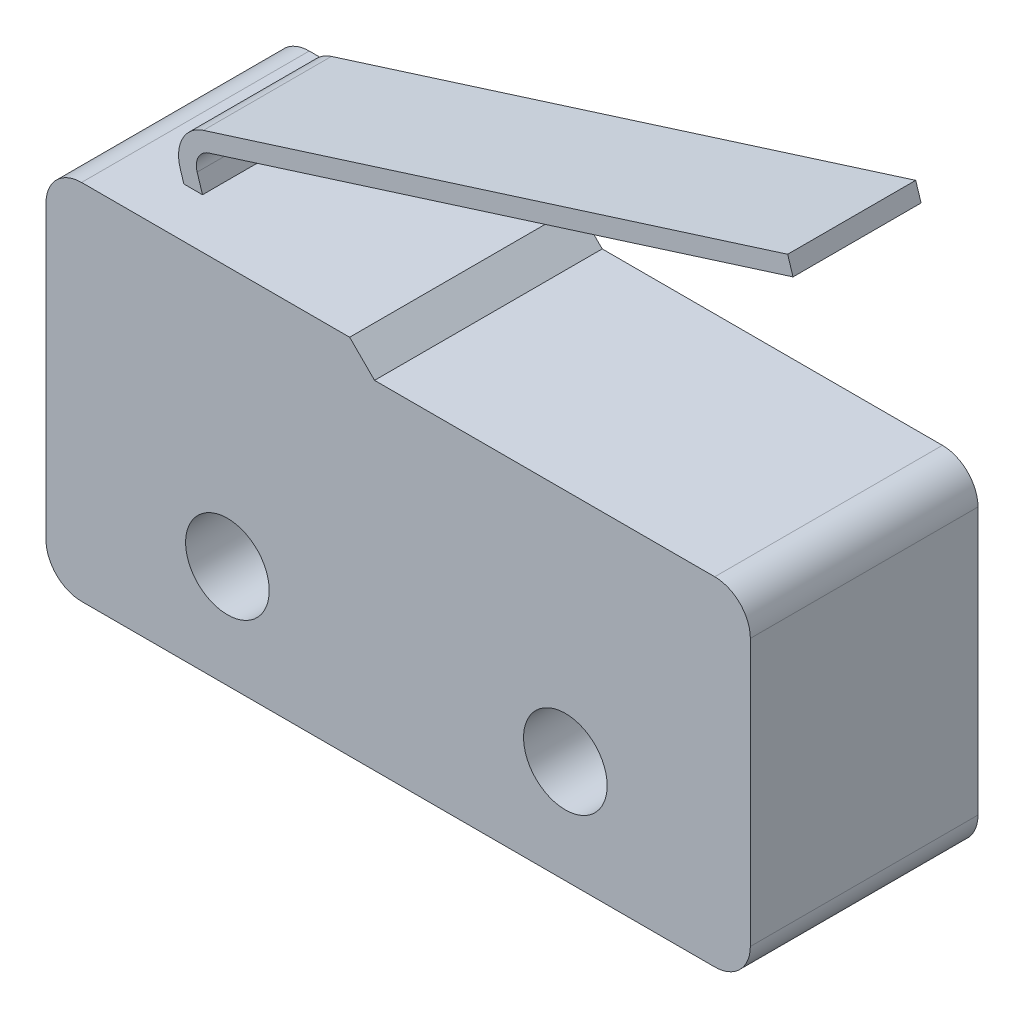
SolidWorks part; units mm, degrees
ref_plane "Plan de face" through (0, 0, 0) normal (0, 0, 1) x (1, 0, 0)
ref_plane "Plan de dessus" through (0, 0, 0) normal (0, 1, 0) x (1, 0, 0)
ref_plane "Plan de droite" through (0, 0, 0) normal (1, 0, 0) x (0, 0, -1)
sketch "Esquisse1" plane through (0, 0, 0) normal (0, 0, 1) x (1, 0, 0)
  line L0 (-71.4594, 0) -> (71.4594, 0) construction
  line L1 (0, 42.166) -> (0, -42.6607) construction
  line L2 (19.8, -5.8117) -> (19.8, 9.5) construction
  line L3 (19.8, 9.5) -> (-68.489, 9.5) construction
  line L4 (-30.4315, 10.2) -> (25.9547, 10.2) construction
  line L5 (-10.1523, 2.9) -> (47.4705, 2.9) construction
  line L6 (5.1, 16.9406) -> (5.1, -11.4998) construction
  line L7 (14.6, 16.9406) -> (14.6, -11.4998) construction
  line L8 (1, 0) -> (18.8, 0)
  line L9 (19.8, 1) -> (19.8, 8.5)
  line L10 (18.8, 9.5) -> (9.236, 9.5)
  line L11 (9.236, 9.5) -> (8.536, 10.2)
  line L12 (8.536, 10.2) -> (1, 10.2)
  line L13 (0, 9.2) -> (0, 1)
  circle A0 centre (5.1, 2.9) radius 1.175
  circle A1 centre (14.6, 2.9) radius 1.175
  arc A2 (0, 1) -> (1, 0) centre (1, 1) ccw
  arc A3 (18.8, 0) -> (19.8, 1) centre (18.8, 1) ccw
  arc A4 (19.8, 8.5) -> (18.8, 9.5) centre (18.8, 8.5) ccw
  arc A5 (0, 9.2) -> (1, 10.2) centre (1, 9.2) cw
  point P27 (0, 0)
  point P30 (19.8, 0)
  point P36 (0, 10.2)
  dimension "D7" = 2.35
  dimension "D8" = 2.35
  dimension "D9" = 1
  dimension "D1" = 2.9
  dimension "D2" = 9.5
  dimension "D3" = 5.1
  dimension "D4" = 19.8
  dimension "D5" = 9.5
  dimension "D6" = 10.2
extrude "Boss.-Extru.1" add sketch "Esquisse1" along normal blind 6.4
ref_plane "Plan1" through (0, 0, 5) normal (0, 0, 1) x (1, 0, 0)
sketch "Esquisse2" plane through (0, 0, 5) normal (0, 0, 1) x (1, 0, 0)
  line L0 (2.4756, 10.2) -> (2.0709, 11.4793) construction
  line L1 (8.536, 10.2) -> (1, 10.2) construction
  line L2 (2.0709, 11.4793) -> (19.4492, 16.9767) construction
  line L3 (19.4492, 16.9767) -> (19.6, 16.5) construction
  line L4 (19.6, 16.5) -> (2.6984, 11.1534) construction
  line L5 (2.6984, 11.1534) -> (3, 10.2) construction
  line L6 (3, 10.2) -> (2.4756, 10.2) construction
  line L9 (-5.813, 2.9) -> (27.2982, 2.9) construction
  line L10 (0, 9.2) -> (0, 1) construction
  line L11 (2.4756, 10.2) -> (2.3725, 10.5259)
  line L12 (3.0243, 11.781) -> (19.4492, 16.9767)
  line L13 (19.4492, 16.9767) -> (19.6, 16.5)
  line L14 (19.6, 16.5) -> (3.1751, 11.3042)
  line L15 (2.8492, 10.6767) -> (3, 10.2)
  line L16 (3, 10.2) -> (2.4756, 10.2)
  circle A0 centre (5.1, 2.9) radius 1.175 construction
  arc A1 (2.3725, 10.5259) -> (3.0243, 11.781) centre (3.3259, 10.8275) cw
  arc A2 (2.8492, 10.6767) -> (3.1751, 11.3042) centre (3.3259, 10.8275) cw
  point P12 (6.275, 2.9)
  point P13 (5.1, 2.9)
  point P14 (14.6, 2.9)
  dimension "D7" = 1
  dimension "D8" = 0.5
  dimension "D1" = 0.5
  dimension "D2" = 13.6
  dimension "D3" = 1
  dimension "D4" = 14.5
  dimension "D5" = 3
  dimension "D6" = 0.5
extrude "Boss.-Extru.2" add sketch "Esquisse2" against normal blind 3.6
